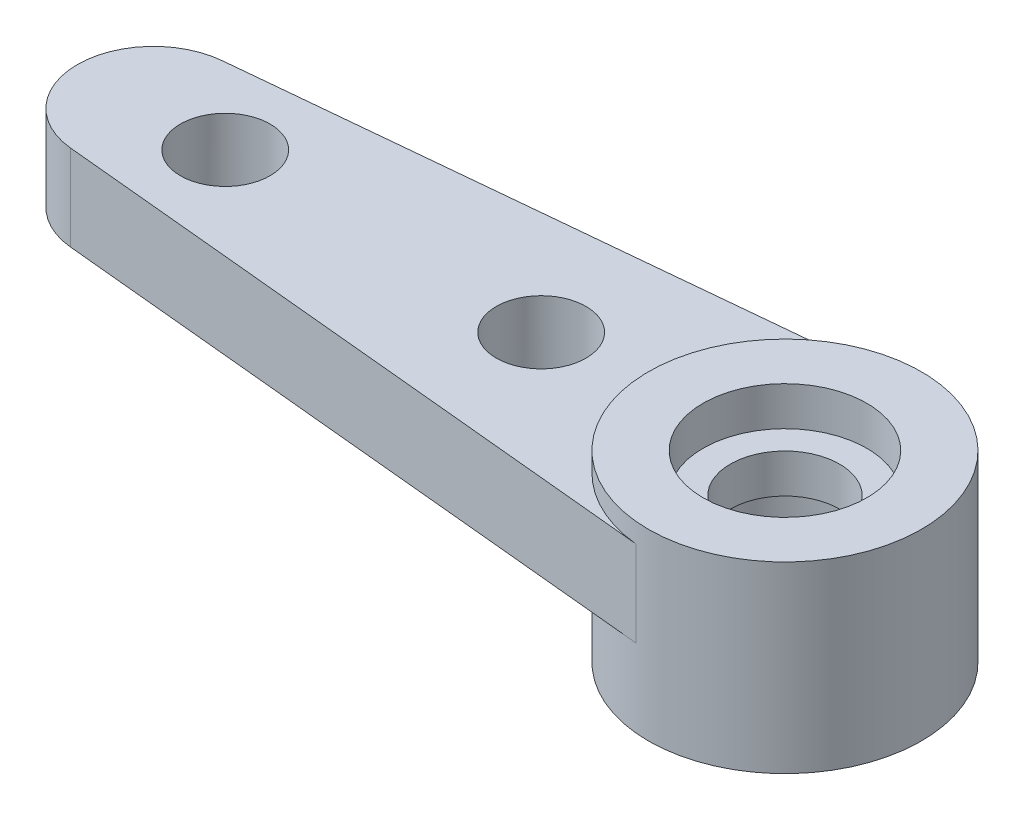
SolidWorks part; units mm, degrees
ref_plane "前基準面" through (0, 0, 0) normal (0, 0, 1) x (1, 0, 0)
ref_plane "上基準面" through (0, 0, 0) normal (0, 1, 0) x (1, 0, 0)
ref_plane "右基準面" through (0, 0, 0) normal (1, 0, 0) x (0, 0, -1)
sketch "Sketch1" plane through (0, 0, 0) normal (0, 1, 0) x (1, 0, 0)
  circle A0 centre (0, 0) radius 2.1
  circle A1 centre (0, 0) radius 3.5
  dimension "D1" = 4.2
  dimension "D2" = 7
extrude "Boss-Extrude1" add sketch "Sketch1" along normal blind 4.7
sketch "Sketch3" plane through (0, 4.7, 0) normal (0, 1, 0) x (1, 0, 0)
  circle A0 centre (0, 0) radius 2.1
  circle A1 centre (0, 0) radius 1.4
  dimension "D1" = 4.2
  dimension "D2" = 2.8
extrude "Boss-Extrude2" add sketch "Sketch3" against normal blind 1 from offset 1 offset against normal yes
sketch "Sketch4" plane through (0, 4.7, 0) normal (0, 1, 0) x (1, 0, 0)
  line L0 (0, 0) -> (-16.19, 0) construction
  line L1 (-18.14, 0) -> (3.5, 0) construction
  line L2 (-0.3351, 3.4839) -> (-16.3767, 1.941)
  line L3 (-0.3351, -3.4839) -> (-16.3767, -1.941)
  circle A0 centre (-16.19, 0) radius 1.95 construction
  circle A1 centre (0, 0) radius 3.5 construction
  arc A2 (-16.3767, -1.941) -> (-16.3767, 1.941) centre (-16.19, 0) cw
  arc A3 (-0.3351, -3.4839) -> (-0.3351, 3.4839) centre (0, 0) cw
  dimension "D1" = 3.9
  dimension "D2" = 21.64
extrude "Boss-Extrude3" add sketch "Sketch4" against normal blind 2.2 from offset 0.5 offset against normal yes
sketch "Sketch5" plane through (0, 4.2, 0) normal (0, 1, 0) x (1, 0, 0)
  line L0 (0, 0) -> (-18.14, 0) construction
  arc A0 (-16.3767, 1.941) -> (-16.3767, -1.941) centre (-16.19, 0) ccw construction
  circle A1 centre (-14.35, 0) radius 1.15
  circle A2 centre (-6.25, 0) radius 1.15
  circle A3 centre (0, 0) radius 1.4 construction
  dimension "D1" = 2.3
  dimension "D2" = 6.25
  dimension "D3" = 8.1
extrude "Cut-Extrude1" cut sketch "Sketch5" against normal up to next
